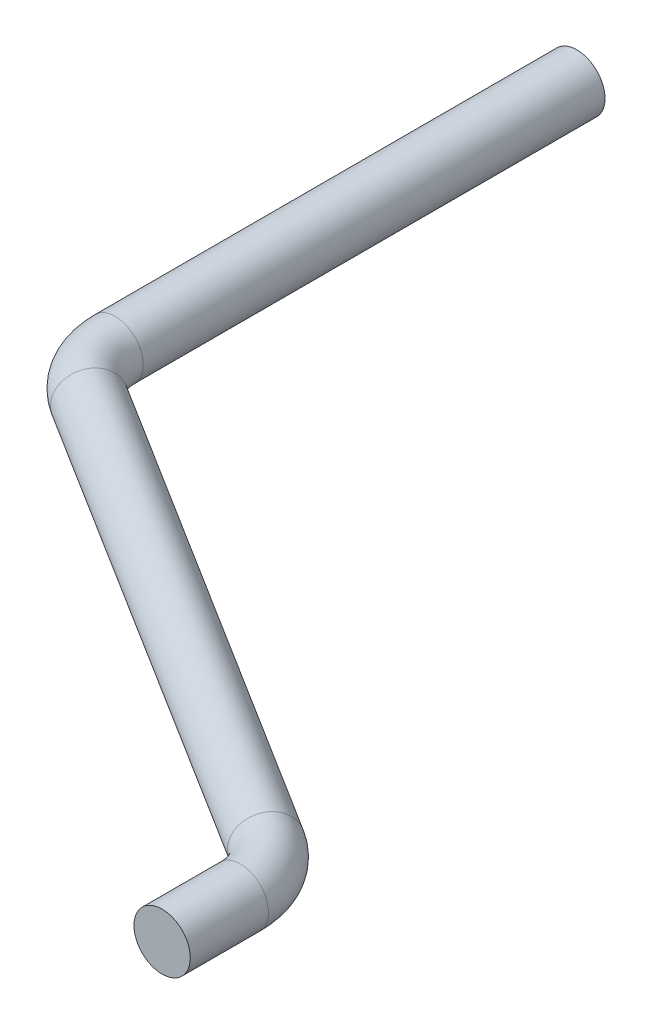
SolidWorks part; units mm, degrees
ref_plane "Alzado" through (0, 0, 0) normal (0, 0, 1) x (1, 0, 0)
ref_plane "Planta" through (0, 0, 0) normal (0, 1, 0) x (1, 0, 0)
ref_plane "Vista lateral" through (0, 0, 0) normal (1, 0, 0) x (0, 0, -1)
sketch3d "Croquis3D1"
  line L0 (22.6979, -725.4886, 1717.536) -> (22.6979, -725.4886, 1671.7288)
  line L2 (3.9159, -725.4886, 1637.8202) -> (-272.8778, -725.4886, 1464.6192)
  line L3 (-291.6598, -725.4886, 1430.7106) -> (-291.6598, -725.4886, 1160.3102)
  line L4 (-187.3021, -725.4886, 1717.536) -> (-187.3021, -725.4886, 1590.9411)
  line L6 (-397.3021, -725.4886, 1717.536) -> (-397.3021, -725.4886, 1154.3719)
  line L8 (-205.5503, -725.4886, 1557.3724) -> (-318.6079, -725.4886, 1484.1135)
  line L9 (-336.8561, -725.4886, 1450.5448) -> (-336.8561, -725.4886, 1156.1709)
  arc A0 (-318.6079, -725.4886, 1484.1135) -> (-336.8561, -725.4886, 1450.5448) centre (-296.8561, -725.4886, 1450.5448) ccw
  arc A1 (-272.8778, -725.4886, 1464.6192) -> (-291.6598, -725.4886, 1430.7106) centre (-251.6598, -725.4886, 1430.7106) ccw
  arc A2 (-187.3021, -725.4886, 1590.9411) -> (-205.5503, -725.4886, 1557.3724) centre (-227.3021, -725.4886, 1590.9411) ccw
  arc A3 (22.6979, -725.4886, 1671.7288) -> (3.9159, -725.4886, 1637.8202) centre (-17.3021, -725.4886, 1671.7288) ccw
  point P17 (-336.8561, -725.4886, 1472.2891)
  point P18 (-296.8561, -765.4886, 1450.5448)
  point P22 (-291.6598, -725.4886, 1452.8666)
  point P23 (-251.6598, -765.4886, 1430.7106)
  point P26 (-187.3021, -725.4886, 1569.1968)
  point P27 (-227.3021, -685.4886, 1590.9411)
  point P30 (22.6979, -725.4886, 1649.5728)
  point P31 (-17.3021, -685.4886, 1671.7288)
  dimension "D1" = 40
sweep "Barrer1" add path "Croquis3D1" circular profile diameter 33 parameters "D3"=33
